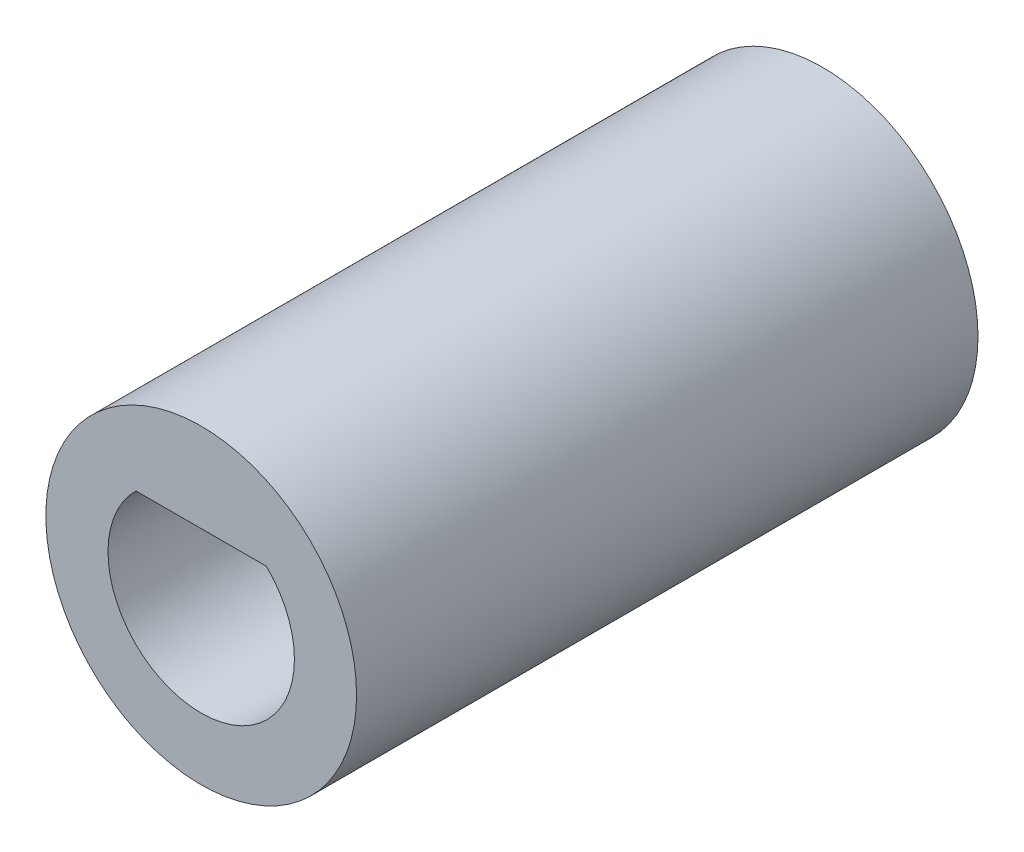
SolidWorks part; units mm, degrees
ref_plane "前视基准面" through (0, 0, 0) normal (0, 0, 1) x (1, 0, 0)
ref_plane "上视基准面" through (0, 0, 0) normal (0, 1, 0) x (1, 0, 0)
ref_plane "右视基准面" through (0, 0, 0) normal (1, 0, 0) x (0, 0, -1)
other "Configuration Table"
sketch "草图1" plane through (0, 0, 0) normal (0, 0, 1) x (1, 0, 0)
  circle A0 centre (0, 0) radius 3.5
  dimension "D1" = 7
extrude "凸台-拉伸1" add sketch "草图1" along normal blind 14
sketch "草图2" plane through (0, 0, 14) normal (0, 0, 1) x (1, 0, 0)
  line L0 (-1.4697, 1.5) -> (1.4697, 1.5)
  circle A0 centre (0, 0) radius 2.1
  dimension "D1" = 4.2
  dimension "D2" = 1.5
extrude "切除-拉伸1" cut sketch "草图2" against normal blind 7 contours L0 A0
sketch "草图3" plane through (0, 0, 0) normal (0, 0, -1) x (-1, 0, 0)
  line L1 (0.95, -2.45) -> (-0.95, -2.45)
  line L2 (0.95, -2.45) -> (0.95, 2.45)
  line L3 (0.95, 2.45) -> (-0.95, 2.45)
  line L4 (-0.95, -2.45) -> (-0.95, 2.45)
  line L5 (0.95, -2.45) -> (-0.95, 2.45) construction
  line L6 (0.95, 2.45) -> (-0.95, -2.45) construction
  line L7 (-2.45, -0.95) -> (2.45, -0.95)
  line L8 (-2.45, -0.95) -> (-2.45, 0.95)
  line L9 (-2.45, 0.95) -> (2.45, 0.95)
  line L10 (2.45, -0.95) -> (2.45, 0.95)
  line L11 (-2.45, -0.95) -> (2.45, 0.95) construction
  line L12 (-2.45, 0.95) -> (2.45, -0.95) construction
  point P0 (0, 0)
  point P6 (0, 0)
  dimension "D1" = 4.9
  dimension "D2" = 1.9
extrude "切除-拉伸2" cut sketch "草图3" against normal blind 6 contours L7 L4 L1 L2 | L7 L10 L9 L2 | L9 L4 L7 L2 | L9 L8 L7 L4 | L4 L9 L2 L3
fillet "圆角2" radius 0.1 36 edges at (0, 2.45, 0) (-1.7, 0.95, 0) (0, -2.45, 0) (2.45, 0, 0) (0.95, 2.45, 3) (0.95, 1.7, 0) (0.95, 0.95, 3) (2.45, 0.95, 3) (1.7, 0.95, 0) (-1.7, -0.95, 0) (-2.45, -0.95, 3) (-2.45, 0.95, 3) (-2.45, 0, 0) (-0.95, 0.95, 3) (-0.95, 2.45, 3) (-0.95, 1.7, 0) (-0.95, -2.45, 3) (-0.95, -0.95, 3) (-0.95, -1.7, 0) (2.45, -0.95, 3) (1.7, -0.95, 0) (0.95, -0.95, 3) (0.95, -2.45, 3) (0.95, -1.7, 0) (0, -2.45, 6) (0.95, -1.7, 6) (1.7, -0.95, 6) (2.45, 0, 6) (1.7, 0.95, 6) (0.95, 1.7, 6) (0, 2.45, 6) (-0.95, 1.7, 6) (-1.7, 0.95, 6) (-2.45, 0, 6) (-1.7, -0.95, 6) (-0.95, -1.7, 6)
